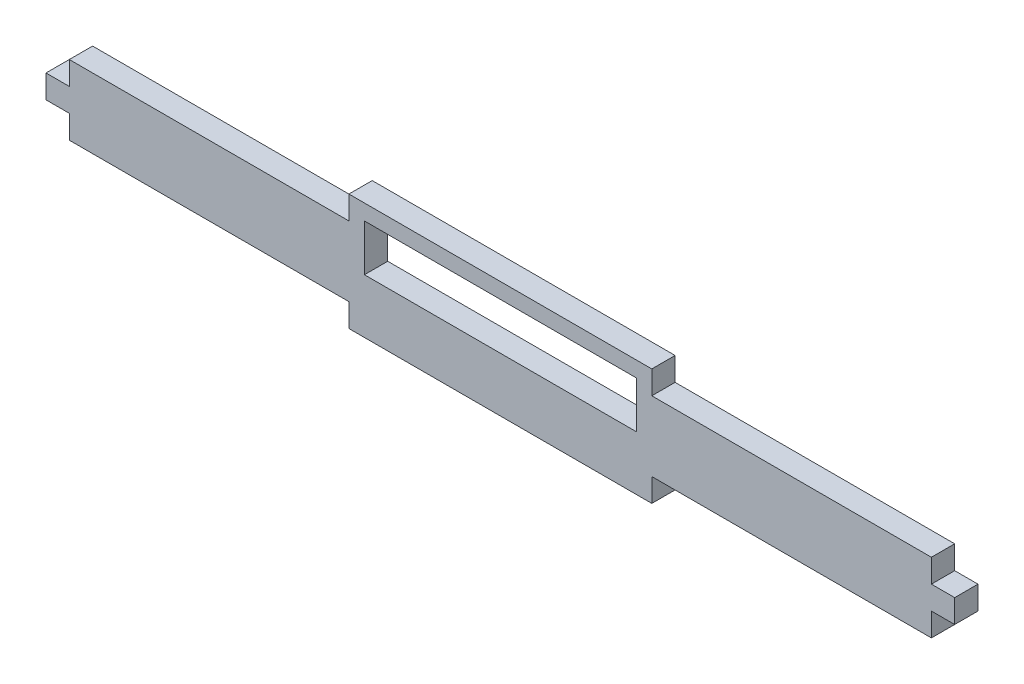
SolidWorks part; units mm, degrees
ref_plane "Front Plane" through (0, 0, 0) normal (0, 0, 1) x (1, 0, 0)
ref_plane "Top Plane" through (0, 0, 0) normal (0, 1, 0) x (1, 0, 0)
ref_plane "Right Plane" through (0, 0, 0) normal (1, 0, 0) x (0, 0, -1)
sketch "Sketch1" plane through (0, 0, 0) normal (0, 0, 1) x (1, 0, 0)
  line L1 (-58.5, -7.5) -> (58.5, -7.5) construction
  line L2 (-58.5, -7.5) -> (-58.5, 7.5) construction
  line L3 (-58.5, 7.5) -> (58.5, 7.5) construction
  line L4 (58.5, -7.5) -> (58.5, 7.5) construction
  line L5 (-58.5, -7.5) -> (58.5, 7.5) construction
  line L6 (-58.5, 7.5) -> (58.5, -7.5) construction
  line L11 (-46.4777, -5.9587) -> (46.4777, 5.9587) construction
  line L12 (-46.4777, 5.9587) -> (46.4777, -5.9587) construction
  line L14 (-19.5, -7.5) -> (19.5, -7.5)
  line L19 (58.5, -1.5) -> (58.5, 1.5)
  line L24 (19.5, 7.5) -> (-19.5, 7.5)
  line L29 (-58.5, 1.5) -> (-58.5, -1.5)
  line L32 (-19.5, -7.5) -> (-19.5, -4.5)
  line L33 (-19.5, -4.5) -> (-58.5, -4.5) construction
  line L34 (-19.5, 7.5) -> (-19.5, 4.5)
  line L35 (-19.5, 4.5) -> (-58.5, 4.5) construction
  line L38 (19.5, 7.5) -> (19.5, 4.5)
  line L39 (19.5, 4.5) -> (58.5, 4.5) construction
  line L42 (58.5, -4.5) -> (19.5, -4.5) construction
  line L43 (19.5, -4.5) -> (19.5, -7.5)
  line L44 (58.5, 1.5) -> (55.5, 1.5)
  line L45 (55.5, 1.5) -> (55.5, 4.5)
  line L46 (58.5, -1.5) -> (55.5, -1.5)
  line L47 (55.5, -1.5) -> (55.5, -4.5)
  line L48 (-58.5, 1.5) -> (-55.5, 1.5)
  line L49 (-55.5, 1.5) -> (-55.5, 4.5)
  line L50 (-58.5, -1.5) -> (-55.5, -1.5)
  line L51 (-55.5, -1.5) -> (-55.5, -4.5)
  line L52 (19.5, 4.5) -> (55.5, 4.5)
  line L53 (55.5, -4.5) -> (19.5, -4.5)
  line L54 (-55.5, 4.5) -> (-19.5, 4.5)
  line L55 (-19.5, -4.5) -> (-55.5, -4.5)
  line L57 (-17.5, -0.5) -> (17.5, -0.5)
  line L58 (-17.5, -0.5) -> (-17.5, 5.5)
  line L59 (-17.5, 5.5) -> (17.5, 5.5)
  line L60 (17.5, -0.5) -> (17.5, 5.5)
  line L61 (-17.5, -0.5) -> (17.5, 5.5) construction
  line L62 (-17.5, 5.5) -> (17.5, -0.5) construction
  point P0 (0, 0)
  point P6 (0, 0)
  point P35 (0, 0)
  point P40 (0.3244, 2.9546)
  point P42 (0, 2.5)
  dimension "D1" = 117
  dimension "D2" = 15
  dimension "D3" = 3
  dimension "D4" = 35
  dimension "D5" = 6
  dimension "D6" = 2.5
extrude "Boss-Extrude1" add sketch "Sketch1" along normal blind 3
